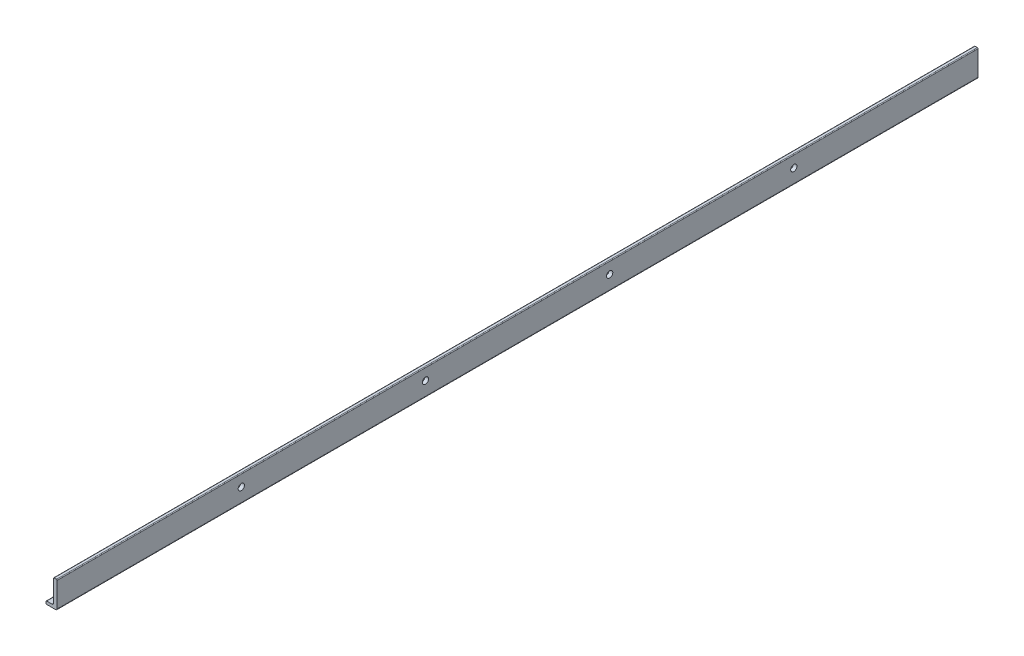
SolidWorks part; units mm, degrees
material "1.4511 (X3CrNb17)"
ref_plane "前视基准面" through (0, 0, 0) normal (0, 0, 1) x (1, 0, 0)
ref_plane "上视基准面" through (0, 0, 0) normal (0, 1, 0) x (1, 0, 0)
ref_plane "右视基准面" through (0, 0, 0) normal (1, 0, 0) x (0, 0, -1)
sketch "草图1" plane through (0, 0, 0) normal (0, 0, 1) x (1, 0, 0)
  line L0 (0, 0) -> (0, 18)
  line L1 (0, 18) -> (-2.5, 18)
  line L2 (-2.5, 18) -> (-2.5, 2)
  line L3 (-2.5, 2) -> (-7.5, 2)
  line L4 (-7.5, 2) -> (-7.5, 0)
  line L5 (-7.5, 0) -> (0, 0)
  dimension "D1" = 18
  dimension "D2" = 2.5
  dimension "D3" = 16
  dimension "D4" = 5
extrude "凸台-拉伸1" add sketch "草图1" along normal blind 620
sketch "草图2" plane through (0, 0, 0) normal (1, 0, 0) x (0, 0, -1)
  line L1 (-620, 0) -> (0, 0) construction
  line L2 (-620, 0) -> (-620, 18) construction
  point P2 (-496, 10)
  point P7 (-372, 10)
  point P8 (-248, 10)
  point P9 (-124, 10)
  dimension "D1" = 10
  dimension "D2" = 124
  dimension "D3" = 4
hole_wizard "M5 螺纹孔1" positions "草图3" profile "草图5" tap size "M5" standard "GB" end condition through all
sketch "草图3" plane through (0, 0, 0) normal (1, 0, 0) x (0, 0, -1)
  point P0 (-496, 10)
  point P3 (-372, 10)
  point P6 (-248, 10)
  point P9 (-124, 10)
sketch "草图5" plane through (0, 10, 496) normal (0, 1, 0) x (0, 0, -1)
  line L0 (0, 0) -> (0, 7.5)
  line L1 (0, 7.5) -> (2.1, 7.5)
  line L2 (2.1, 7.5) -> (2.1, 0)
  line L5 (2.1, 0) -> (0, 0)
  line L11 (0, -6.35) -> (0, 107.95) construction
  dimension "通孔螺纹孔钻头直径" = 4.2
  dimension "通孔螺纹孔钻头深度" = 7.5
cosmetic thread "孔螺蚊线1" parameters "D2"=5
cosmetic thread "孔螺蚊线2" parameters "D2"=5
cosmetic thread "孔螺蚊线3" parameters "D2"=5
cosmetic thread "孔螺蚊线4" parameters "D2"=5
fillet "圆角1" radius 1 2 edges at (-2.5, 2, 310) (0, 0, 310)
fillet "圆角2" radius 0.5 4 edges at (-7.5, 0, 310) (-7.5, 2, 310) (-2.5, 18, 310) (0, 18, 310)
